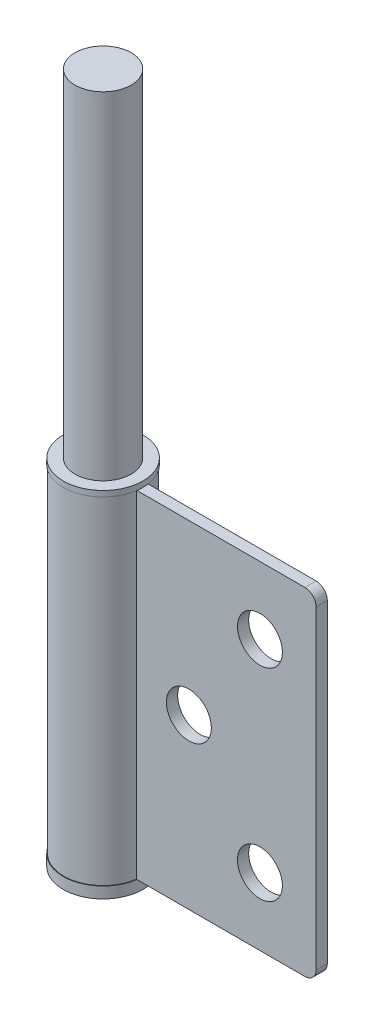
SolidWorks part; units mm, degrees
ref_plane "前视基准面" through (0, 0, 0) normal (0, 0, 1) x (1, 0, 0)
ref_plane "上视基准面" through (0, 0, 0) normal (0, 1, 0) x (1, 0, 0)
ref_plane "右视基准面" through (0, 0, 0) normal (1, 0, 0) x (0, 0, -1)
sketch "草图1" plane through (0, 0, 0) normal (0, 1, 0) x (1, 0, 0)
  line L0 (0, 0) -> (9.9203, 0) construction
  line L2 (19.4641, -0.5) -> (3.4641, -0.5)
  line L3 (19.4641, -0.5) -> (19.4641, 0.5)
  line L4 (19.4641, 0.5) -> (3.4641, 0.5)
  line L6 (19.4641, -0.5) -> (3.4641, 0.5) construction
  line L7 (19.4641, 0.5) -> (3.4641, -0.5) construction
  arc A0 (3.4641, 0.5) -> (3.4641, -0.5) centre (0, 0) ccw
  circle A1 centre (0, 0) radius 2.5
  point P4 (11.4641, 0)
  dimension "D2" = 7
  dimension "D4" = 5
  dimension "D1" = 1
  dimension "D3" = 16
extrude "凸台-拉伸1" add sketch "草图1" along normal blind 30
sketch "草图2" plane through (0, 0, 0.5) normal (0, 0, 1) x (1, 0, 0)
  line L0 (19.4641, 15) -> (3.4641, 15) construction
  line L1 (19.4641, 30) -> (19.4641, 0) construction
  line L2 (3.4641, 30) -> (3.4641, 0) construction
  circle A0 centre (14.4641, 24) radius 2
  circle A1 centre (8.1395, 15) radius 2
  circle A2 centre (14.4641, 6) radius 2
  dimension "D1" = 4
  dimension "D5" = 4
  dimension "D2" = 18
  dimension "D3" = 11
  dimension "D4" = 5
extrude "切除-拉伸1" cut sketch "草图2" against normal up to next
fillet "圆角1" radius 1 2 edges at (19.4641, 30, 0) (19.4641, 0, 0)
sketch "草图3" plane through (0, 0, 0) normal (0, -1, 0) x (1, 0, 0)
  circle A0 centre (0, 0) radius 2.5
extrude "凸台-拉伸2" add sketch "草图3" against normal blind 60.5
sketch "草图4" plane through (0, 0, 0) normal (0, -1, 0) x (1, 0, 0)
  circle A0 centre (0, 0) radius 3.55
  dimension "D1" = 7.1
extrude "凸台-拉伸3" add sketch "草图4" along normal blind 1
sketch "草图5" plane through (0, 30, 0) normal (0, 1, 0) x (1, 0, 0)
  circle A0 centre (0, 0) radius 2.5
  circle A1 centre (0, 0) radius 3.55
extrude "凸台-拉伸4" add sketch "草图5" along normal blind 0.5
